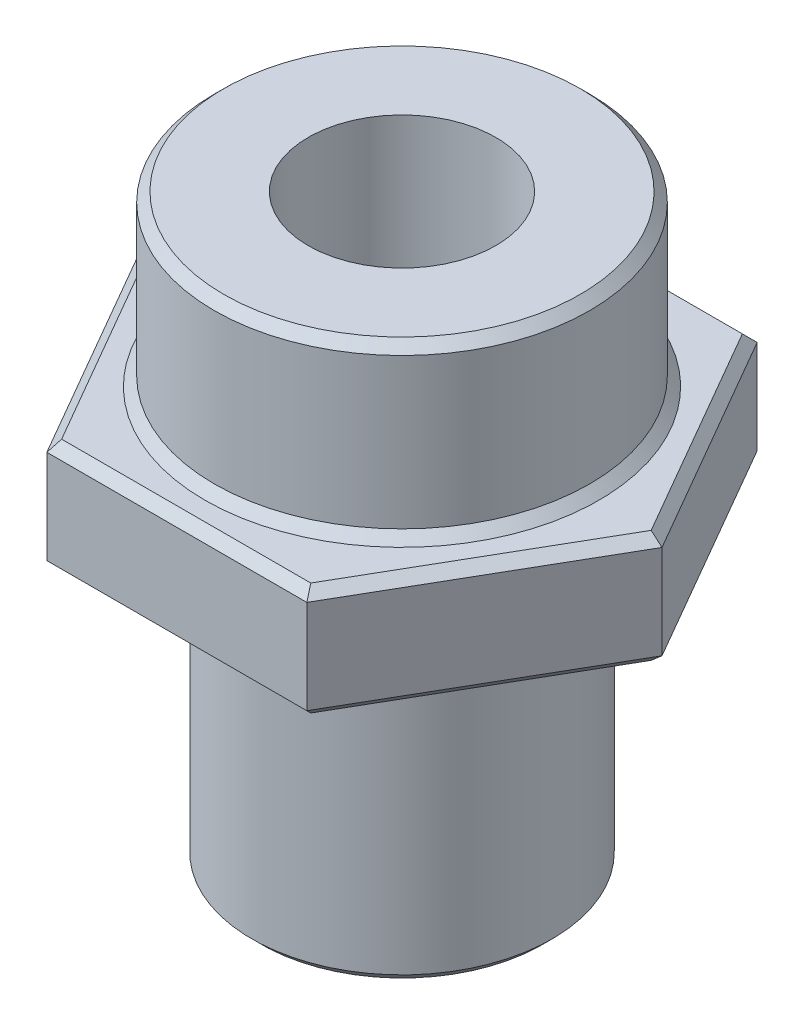
SolidWorks part; units mm, degrees
ref_plane "Front Plane" through (0, 0, 0) normal (0, 0, 1) x (1, 0, 0)
ref_plane "Top Plane" through (0, 0, 0) normal (0, 1, 0) x (1, 0, 0)
ref_plane "Right Plane" through (0, 0, 0) normal (1, 0, 0) x (0, 0, -1)
sketch "Sketch3" plane through (0, 0, 0) normal (0, 0, 1) x (1, 0, 0)
  line L1 (-5, 0) -> (-5, -4.5)
  line L2 (-5, -4.5) -> (-6, -4.5)
  line L3 (-6, -4.5) -> (-6, -7.5)
  line L4 (-6, -7.5) -> (-4, -7.5)
  line L5 (-4, -7.5) -> (-4, -15.5)
  line L6 (-4, -15.5) -> (-2.5, -15.5)
  line L8 (-5, 0) -> (-2.5, 0)
  line L9 (-2.5, 0) -> (-2.5, -15.5)
  line L10 (0, 0) -> (0, -15.5) construction
  dimension "D1" = 2.5
  dimension "D2" = 5
  dimension "D3" = 6
  dimension "D4" = 4.5
  dimension "D5" = 3
  dimension "D6" = 8
  dimension "D7" = 4
revolve "Revolve1" add sketch "Sketch3" angle 360 about L10
sketch "Sketch4" plane through (0, -4.5, 0) normal (0, 1, 0) x (1, 0, 0)
  line L1 (-3.4641, 6) -> (-6.9282, 0)
  line L2 (-6.9282, 0) -> (-3.4641, -6)
  line L3 (-3.4641, -6) -> (3.4641, -6)
  line L4 (3.4641, -6) -> (6.9282, 0)
  line L5 (6.9282, 0) -> (3.4641, 6)
  line L6 (3.4641, 6) -> (-3.4641, 6)
  circle A0 centre (0, 0) radius 6 construction
  dimension "D1" = 12
extrude "Boss-Extrude1" add sketch "Sketch4" against normal up to surface (3 mm away) up to face at (0, -7.5, 4)
chamfer "Chamfer1" distance 0.25 angle 45 16 edges at (0, -4.5, 6) (-5.1962, -4.5, 3) (-5.1962, -4.5, -3) (0, -4.5, -6) (5.1962, -4.5, -3) (5.1962, -4.5, 3) (-5.1962, -7.5, -3) (-5.1962, -7.5, 3) (0, -7.5, 6) (5.1962, -7.5, 3) (5.1962, -7.5, -3) (0, -7.5, -6) (0, -15.5, 4) (0, -7.5, 4) (0, -4.5, 5) (0, 0, 5)
